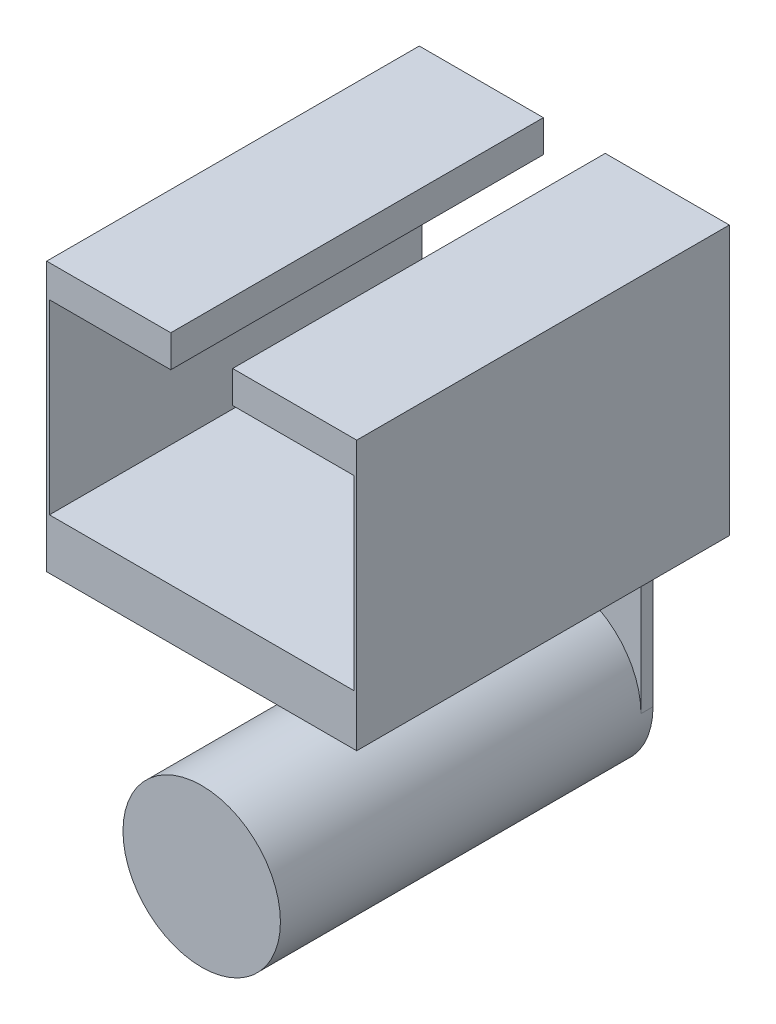
SolidWorks part; units mm, degrees
ref_plane "Front Plane" through (0, 0, 0) normal (0, 0, 1) x (1, 0, 0)
ref_plane "Top Plane" through (0, 0, 0) normal (0, 1, 0) x (1, 0, 0)
ref_plane "Right Plane" through (0, 0, 0) normal (1, 0, 0) x (0, 0, -1)
sketch "Sketch2" plane through (0, 0, 0) normal (0, 0, 1) x (1, 0, 0)
  line L1 (0, 0) -> (32.1996, 0)
  line L2 (0, 0) -> (0, 38.1)
  line L3 (0, 38.1) -> (32.1996, 38.1)
  line L4 (32.1996, 0) -> (32.1996, 38.1)
  dimension "D1" = 38.1
  dimension "D2" = 32.1996
extrude "Boss-Extrude3" add sketch "Sketch2" along normal blind 2.4638
sketch "Sketch4" plane through (0, 0, 0) normal (0, 0, -1) x (-1, 0, 0)
  line L0 (0, 0) -> (-32.1996, 0) construction
  circle A0 centre (-16.0998, 0) radius 16.0998
  dimension "D1" = 32.1996
extrude "Boss-Extrude4" add sketch "Sketch4" against normal blind 76.2
sketch "Sketch5" plane through (0, 38.1, 0) normal (0, 1, 0) x (1, 0, 0)
  line L1 (-15.6045, 0) -> (47.8041, 0)
  line L2 (-15.6045, 0) -> (-15.6045, -76.2)
  line L3 (-15.6045, -76.2) -> (47.8041, -76.2)
  line L4 (47.8041, 0) -> (47.8041, -76.2)
  line L5 (32.1996, 0) -> (0, 0) construction
  point P6 (16.0998, 0)
  point P7 (16.0998, 0)
  dimension "D1" = 63.4086
  dimension "D2" = 76.2
extrude "Boss-Extrude5" add sketch "Sketch5" along normal blind 10.3632
sketch "Sketch6" plane through (0, 48.4632, 0) normal (0, 1, 0) x (1, 0, 0)
  line L0 (47.8041, -76.2) -> (47.8041, 0) construction
  line L1 (47.2402, 0) -> (47.8041, 0)
  line L2 (47.2402, 0) -> (47.2402, -76.2)
  line L3 (47.2402, -76.2) -> (47.8041, -76.2)
  line L4 (47.8041, 0) -> (47.8041, -76.2)
  point P6 (47.8041, -38.1)
  point P7 (47.8041, -38.1)
  dimension "D1" = 0.5639
  dimension "D2" = 76.2
extrude "Boss-Extrude6" add sketch "Sketch6" along normal blind 38.1
sketch "Sketch7" plane through (0, 48.4632, 0) normal (0, 1, 0) x (1, 0, 0)
  line L0 (15.8179, 0) -> (15.8179, -76.2) construction
  line L1 (47.2402, 0) -> (-15.6045, 0) construction
  line L2 (-15.6045, -76.2) -> (47.2402, -76.2) construction
sketch "Sketch8" plane through (0, 48.4632, 0) normal (0, 1, 0) x (1, 0, 0)
  line L0 (-15.6045, 0) -> (-15.6045, -76.2) construction
  line L1 (-15.6045, 0) -> (-15.0406, 0)
  line L2 (-15.6045, 0) -> (-15.6045, -76.2)
  line L3 (-15.6045, -76.2) -> (-15.0406, -76.2)
  line L4 (-15.0406, 0) -> (-15.0406, -76.2)
  point P6 (-15.6045, -38.1)
  point P7 (-15.6045, -38.1)
  dimension "D1" = 0.5639
  dimension "D2" = 76.2
extrude "Boss-Extrude7" add sketch "Sketch8" along normal blind 38.1
sketch "Sketch9" plane through (0, 86.5632, 0) normal (0, 1, 0) x (1, 0, 0)
sketch "Sketch10" plane through (0, 86.5632, 0) normal (0, 1, 0) x (1, 0, 0)
  line L0 (-15.6045, -38.1) -> (47.8041, -38.1) construction
  line L1 (-15.6045, 0) -> (9.7752, 0)
  line L2 (-15.6045, 0) -> (-15.6045, -76.2)
  line L3 (-15.6045, -76.2) -> (9.7752, -76.2)
  line L4 (9.7752, 0) -> (9.7752, -76.2)
  line L5 (-15.6045, 0) -> (-15.6045, -76.2) construction
  line L6 (47.8041, -76.2) -> (47.8041, 0) construction
  point P10 (-15.6045, -38.1)
  dimension "D1" = 25.3797
  dimension "D2" = 76.2
extrude "Boss-Extrude8" add sketch "Sketch10" along normal blind 6.5557
sketch "Sketch12" plane through (0, 86.5632, 0) normal (0, 1, 0) x (1, 0, 0)
  line L0 (15.8179, -38.1) -> (47.8041, -38.1) construction
  line L1 (22.4244, 0) -> (47.8041, 0)
  line L2 (22.4244, 0) -> (22.4244, -76.2)
  line L3 (22.4244, -76.2) -> (47.8041, -76.2)
  line L4 (47.8041, 0) -> (47.8041, -76.2)
  line L5 (15.8179, 0) -> (15.8179, -76.2) construction
  line L6 (47.8041, -76.2) -> (47.8041, 0) construction
  line L7 (22.4244, -38.1) -> (47.8041, -38.1) construction
  dimension "D1" = 25.3797
  dimension "D2" = 76.2
extrude "Boss-Extrude10" add sketch "Sketch12" along normal blind 6.5557
equation "\"F\"= 600"
equation "\"p\"= 2 * \"F\""
equation "\"SF\"= 4"
equation "\"Sy\"= 36000"
equation "\"SigmaAllow\"= \"Sy\" / \"SF\""
equation "\"E\"= 29000000"
equation "\"DeltaAllow\"= 0.005"
equation "\"T_a\"= 0.498'\"T_"
equation "\"T_b\"= 0.9992"
equation "\"T_c\"= 1.499'\"w"
equation "\"Bracket_Width\"= 3"
equation "\"A_Length\"= 3"
equation "\"B_Width\"= 1.375"
equation "\"A_Diameter\"= ( 32 * \"F\" * \"A_Length\" / ( pi * \"SigmaAllow\" ) ) ^ ( 1 / 3 )"
equation "\"B_Thickness\"= \"p\" / ( \"SigmaAllow\" * \"B_Width\" )"
equation "\"C_Length\"= \"T_a\" + 2 * \"T_b\""
equation "\"C_Height\"= ( 1.5 * \"p\" * \"C_Length\" / ( \"Bracket_Width\" * \"SigmaAllow\" ) ) ^ 0.5'."
equation "\"D_Thickness\"= \"F\" / ( \"SigmaAllow\" * \"Bracket_Width\" )"
equation "\"D_Length\"= \"T_c\""
equation "\"E_Length\"= \"T_b\""
equation "\"E_Thickness\"= ( 3 * \"F\" * \"E_Length\" / ( \"Bracket_Width\" * \"SigmaAllow\" ) ) ^ 0.5"
equation "\"B_Height\"= 1.5"
